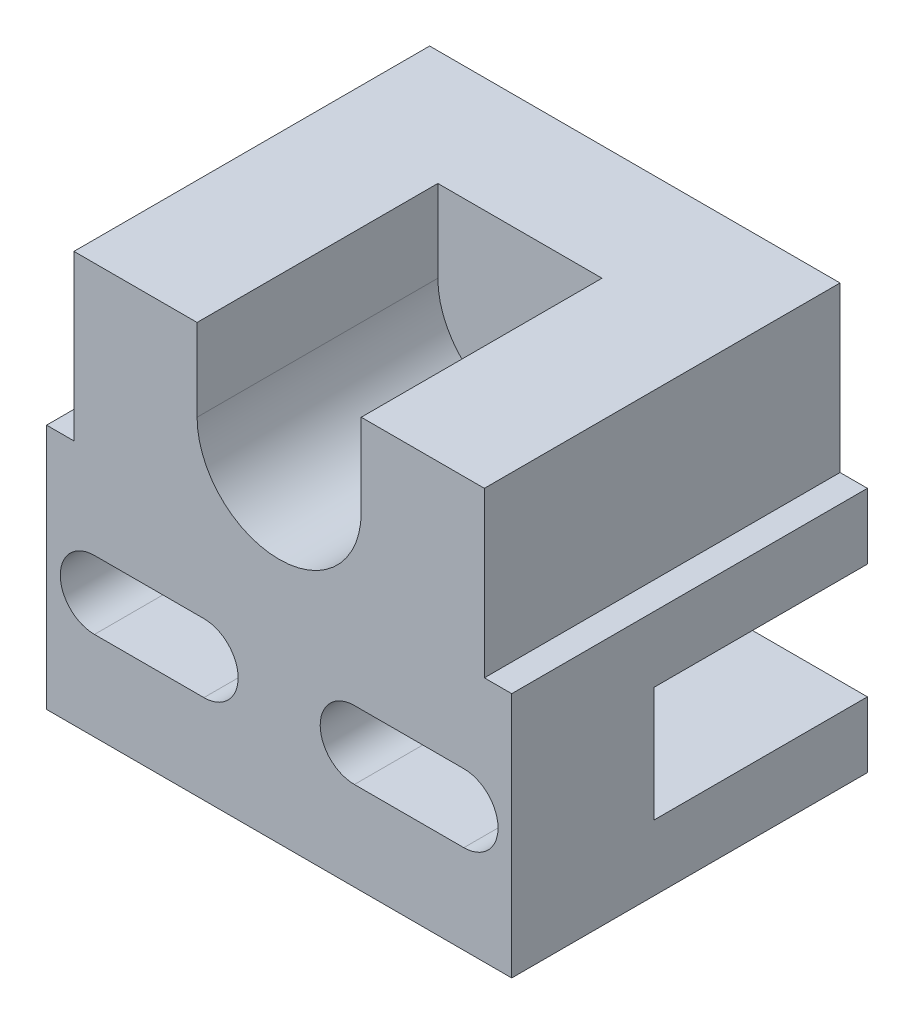
SolidWorks part; units mm, degrees
ref_plane "Front Plane" through (0, 0, 0) normal (0, 0, 1) x (1, 0, 0)
ref_plane "Top Plane" through (0, 0, 0) normal (0, 1, 0) x (1, 0, 0)
ref_plane "Right Plane" through (0, 0, 0) normal (1, 0, 0) x (0, 0, -1)
sketch "Sketch1" plane through (0, 0, 0) normal (0, 0, 1) x (1, 0, 0)
  line L0 (55, 0) -> (-55, 0) construction
  line L1 (-8.5, 0) -> (8.5, 0)
  line L2 (-8.5, 0) -> (-8.5, 9)
  line L3 (-7.5, 15) -> (7.5, 15)
  line L4 (8.5, 0) -> (8.5, 9)
  line L5 (-7.5, 15) -> (-7.5, 9)
  line L6 (-7.5, 9) -> (-8.5, 9)
  line L7 (8.5, 9) -> (7.5, 9)
  line L8 (7.5, 9) -> (7.5, 15)
  dimension "D1" = 17
  dimension "D2" = 15
  dimension "D3" = 15
  dimension "D4" = 9
extrude "Boss-Extrude1" add sketch "Sketch1" along normal blind 13
sketch "Sketch2" plane through (0, 0, 13) normal (0, 0, 1) x (1, 0, 0)
  line L0 (0, 18) -> (0, 12) construction
  line L1 (0, -54.6431) -> (0, 54.6431) construction
  line L2 (3, 18) -> (3, 12)
  line L3 (-3, 18) -> (-3, 12)
  line L4 (55, 0) -> (-55, 0) construction
  line L5 (7.5, 15) -> (-7.5, 15) construction
  arc A0 (3, 18) -> (-3, 18) centre (0, 18) ccw
  arc A1 (-3, 12) -> (3, 12) centre (0, 12) ccw
  point P5 (0, 15)
  dimension "D1" = 6
  dimension "D2" = 12
extrude "Cut-Extrude1" cut sketch "Sketch2" against normal offset from surface (9 mm away) 4 up to face at (0, 8.25, 0)
sketch "Sketch4" plane through (0, 0, 4) normal (0, 0, 1) x (1, 0, 0)
  circle A0 centre (0, 12) radius 1.6
  arc A1 (-3, 12) -> (3, 12) centre (0, 12) ccw construction
  dimension "D1" = 3.2
extrude "Cut-Extrude2" cut sketch "Sketch4" against normal through all
sketch "Sketch5" plane through (0, 0, 13) normal (0, 0, 1) x (1, 0, 0)
  line L0 (0, 0) -> (0, 17.4753) construction
  line L1 (0, -54.6431) -> (0, 54.6431) construction
  line L2 (55, 0) -> (-55, 0) construction
  circle A0 centre (-4.75, 4.5) radius 1.25
  circle A1 centre (4.75, 4.5) radius 1.25
  dimension "D2" = 2.5
  dimension "D1" = 9.5
  dimension "D3" = 4.5
extrude "Cut-Extrude3" cut sketch "Sketch5" against normal through all
sketch "Sketch6" plane through (0, 0, 0) normal (1, 0, 0) x (0, 0, -1)
  line L0 (0, 15) -> (0, 17)
  line L1 (0, 55) -> (0, -55) construction
  line L2 (0, 17) -> (-2, 15)
  line L3 (-2, 15) -> (0, 15)
  line L4 (0, 8) -> (-2, 10)
  line L5 (-2, 10) -> (-2, 0)
  line L6 (55, 0) -> (-55, 0) construction
  line L7 (-2, 0) -> (0, 0)
  line L8 (0, 0) -> (0, 8)
  line L10 (-13, 0) -> (-13, 9) construction
  dimension "D1" = 8
  dimension "D3" = 45
  dimension "D4" = 11
sketch "Sketch7" plane through (0, 0, 13) normal (0, 0, 1) x (1, 0, 0)
  line L0 (-6.75, 4.5) -> (-2.75, 4.5) construction
  line L1 (-6.75, 5.75) -> (-2.75, 5.75)
  line L2 (-6.75, 3.25) -> (-2.75, 3.25)
  line L3 (6.75, 4.5) -> (2.75, 4.5) construction
  line L4 (6.75, 3.25) -> (2.75, 3.25)
  line L5 (6.75, 5.75) -> (2.75, 5.75)
  arc A0 (-6.75, 5.75) -> (-6.75, 3.25) centre (-6.75, 4.5) ccw
  arc A1 (-2.75, 3.25) -> (-2.75, 5.75) centre (-2.75, 4.5) ccw
  arc A2 (6.75, 3.25) -> (6.75, 5.75) centre (6.75, 4.5) ccw
  arc A3 (2.75, 5.75) -> (2.75, 3.25) centre (2.75, 4.5) ccw
  circle A4 centre (4.75, 4.5) radius 1.25 construction
  circle A5 centre (-4.75, 4.5) radius 1.25 construction
  point P2 (-4.75, 4.5)
  point P9 (4.75, 4.5)
  dimension "D1" = 4
extrude "Cut-Extrude4" cut sketch "Sketch7" against normal through all
sketch "Sketch8" plane through (0, 0, 0) normal (0, 0, -1) x (-1, 0, 0)
  line L1 (-1.5376, 6.6) -> (-3.9624, 6.6)
  line L2 (-3.9624, 6.6) -> (-5.1749, 4.5)
  line L3 (-5.1749, 4.5) -> (-3.9624, 2.4)
  line L4 (-3.9624, 2.4) -> (-1.5376, 2.4)
  line L5 (-1.5376, 2.4) -> (-0.3251, 4.5)
  line L6 (-0.3251, 4.5) -> (-1.5376, 6.6)
  line L7 (1.5376, 6.6) -> (0.3251, 4.5)
  line L8 (0.3251, 4.5) -> (1.5376, 2.4)
  line L9 (1.5376, 2.4) -> (3.9624, 2.4)
  line L10 (3.9624, 2.4) -> (5.1749, 4.5)
  line L11 (5.1749, 4.5) -> (3.9624, 6.6)
  line L12 (3.9624, 6.6) -> (1.5376, 6.6)
  circle A0 centre (-2.75, 4.5) radius 2.1 construction
  circle A1 centre (2.75, 4.5) radius 2.1 construction
  dimension "D1" = 4.2
extrude "Cut-Extrude5" cut sketch "Sketch8" against normal offset from surface (7.8 mm away) 5.2 up to face at (4.75, 4.5, 13)
sketch "Sketch9" plane through (0, 0, 7.8) normal (0, 0, -1) x (-1, 0, 0)
  line L0 (-3.9624, 2.4) -> (-1.5376, 2.4) construction
  line L1 (1.5376, 6.6) -> (8.5, 6.6)
  line L2 (1.5376, 6.6) -> (1.5376, 2.4)
  line L3 (1.5376, 2.4) -> (8.5, 2.4)
  line L4 (8.5, 6.6) -> (8.5, 2.4)
  line L5 (-1.5376, 6.6) -> (-8.5, 6.6)
  line L6 (-1.5376, 6.6) -> (-1.5376, 2.4)
  line L7 (-1.5376, 2.4) -> (-8.5, 2.4)
  line L8 (-8.5, 6.6) -> (-8.5, 2.4)
  line L9 (-3.9624, 2.4) -> (-1.5376, 2.4) construction
  line L10 (-8.5, 0) -> (-8.5, 9) construction
  line L11 (8.5, 9) -> (8.5, 0) construction
extrude "Cut-Extrude6" cut sketch "Sketch9" along normal up to surface (7.8 mm away) up to face at (-3.8868, 4.5, 0)
sketch "Sketch10" plane through (0, 0, 0) normal (0, 0, -1) x (-1, 0, 0)
  line L0 (0, 0) -> (0, 8) construction
  line L1 (0, 10) -> (0, 0) construction
  line L2 (0.3251, 4.5) -> (1.5376, 2.4) construction
  circle A0 centre (0, 8.2631) radius 1.4
  circle A1 centre (0, 2.2631) radius 1.4
  dimension "D1" = 2.8
  dimension "D2" = 6
extrude "Boss-Extrude2" add sketch "Sketch10" along normal blind 2.5
chamfer "Chamfer1" distance 0.5 angle 45 2 edges at (-1.4, 2.2631, -2.5) (-1.4, 8.2631, -2.5)
sketch "Sketch11" plane through (0, 0, 4) normal (0, 0, 1) x (1, 0, 0)
  line L3 (3, 15) -> (-3, 15)
  line L4 (-3, 15) -> (-3, 12)
  line L5 (3, 12) -> (3, 15)
  line L6 (3, 15) -> (-3, 15)
  line L7 (-3, 15) -> (-3, 12)
  line L8 (3, 12) -> (3, 15)
  arc A1 (-3, 12) -> (3, 12) centre (0, 12) ccw
  arc A2 (-3, 12) -> (3, 12) centre (0, 12) ccw
  dimension "D1" = 0
extrude "Boss-Extrude3" add sketch "Sketch11" along normal blind 0.2
